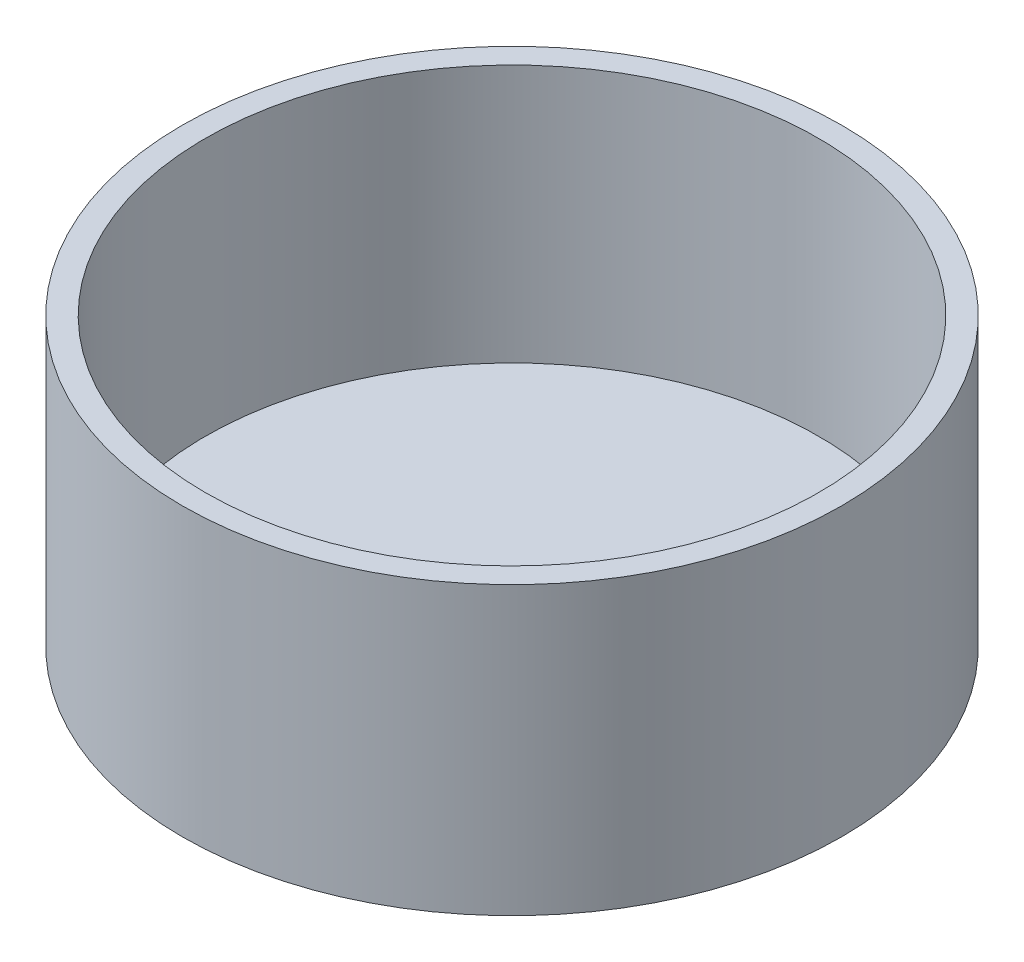
SolidWorks part; units mm, degrees
ref_plane "前视基准面" through (0, 0, 0) normal (0, 0, 1) x (1, 0, 0)
ref_plane "上视基准面" through (0, 0, 0) normal (0, 1, 0) x (1, 0, 0)
ref_plane "右视基准面" through (0, 0, 0) normal (1, 0, 0) x (0, 0, -1)
sketch "草图1" plane through (0, 0, 0) normal (0, 1, 0) x (1, 0, 0)
  circle A0 centre (0, 0) radius 23 construction
  circle A1 centre (0, 0) radius 21.4
  dimension "D1" = 46
  dimension "D3" = 42.8
  dimension "D2" = 1.6
extrude "凸台-拉伸1" add sketch "草图1" along normal blind 2
sketch "草图2" plane through (0, 0, 0) normal (0, 1, 0) x (1, 0, 0)
  circle A0 centre (0, 0) radius 23 construction
  circle A1 centre (0, 0) radius 23
  circle A2 centre (0, 0) radius 21.4 construction
  circle A3 centre (0, 0) radius 21.4
extrude "凸台-拉伸2" add sketch "草图2" along normal blind 20
